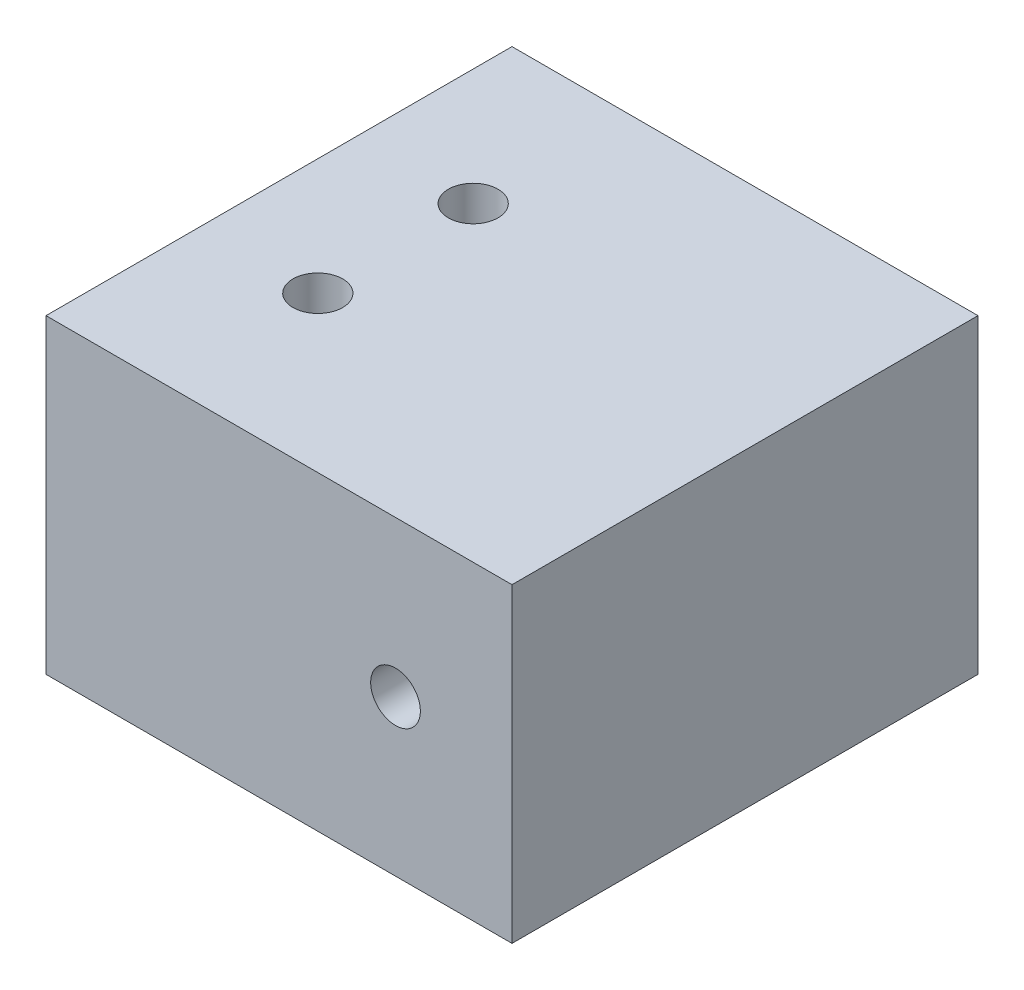
SolidWorks part; units mm, degrees
material "ABS"
ref_plane "前视基准面" through (0, 0, 0) normal (0, 0, 1) x (1, 0, 0)
ref_plane "上视基准面" through (0, 0, 0) normal (0, 1, 0) x (1, 0, 0)
ref_plane "右视基准面" through (0, 0, 0) normal (1, 0, 0) x (0, 0, -1)
other "Configuration Table"
sketch "草图1" plane through (0, 0, 0) normal (0, 1, 0) x (1, 0, 0)
  line L0 (7.5, 36.6638) -> (7.5, -9.8863) construction
  line L1 (0, 0) -> (30, 0)
  line L2 (0, 0) -> (0, 30)
  line L3 (0, 30) -> (30, 30)
  line L4 (30, 0) -> (30, 30)
  circle A0 centre (7.5, 20) radius 1.6
  circle A1 centre (7.5, 10) radius 1.6
  dimension "D4" = 10
  dimension "D5" = 3.2
  dimension "D1" = 30
  dimension "D2" = 7.5
  dimension "D3" = 10
extrude "凸台-拉伸1" add sketch "草图1" along normal blind 20
sketch "草图2" plane through (0, 0, -30) normal (0, 0, -1) x (-1, 0, 0)
  line L0 (-31.9002, 10) -> (1.5699, 10) construction
  line L1 (0, 20) -> (0, 0) construction
  line L2 (-30, 20) -> (-30, 0) construction
  circle A0 centre (-22.5, 10) radius 1.6
  point P4 (0, 10)
  dimension "D1" = 3.2
  dimension "D2" = 7.5
extrude "切除-拉伸1" cut sketch "草图2" against normal through all
